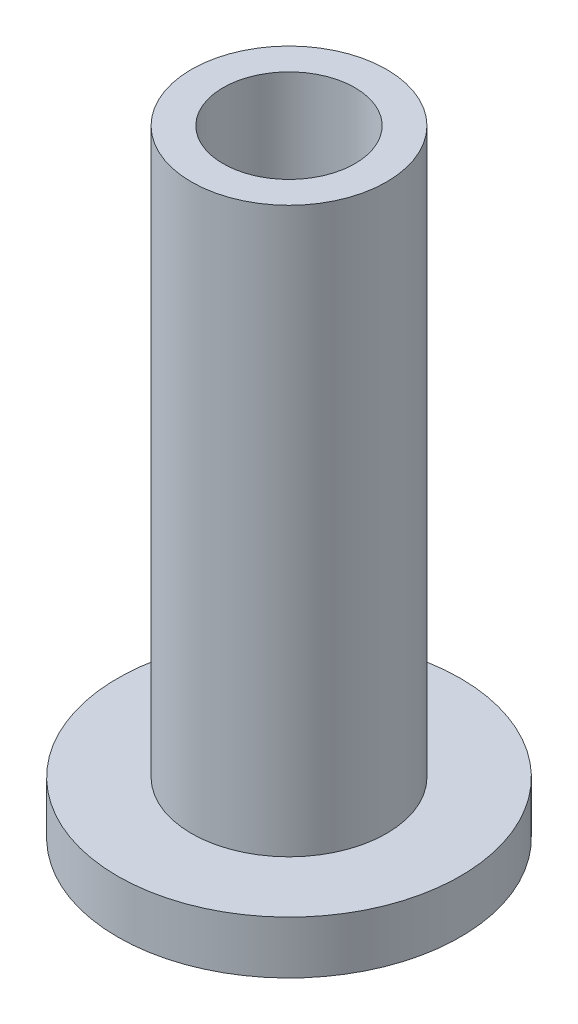
SolidWorks part; units mm, degrees
material "Delrin 2700 NC010, Low Viscosity Acetal Copolymer (SS)"
ref_plane "Front Plane" through (0, 0, 0) normal (0, 0, 1) x (1, 0, 0)
ref_plane "Top Plane" through (0, 0, 0) normal (0, 1, 0) x (1, 0, 0)
ref_plane "Right Plane" through (0, 0, 0) normal (1, 0, 0) x (0, 0, -1)
sketch "Sketch1" plane through (0, 0, 0) normal (0, 1, 0) x (1, 0, 0)
  circle A0 centre (0, 0) radius 4.1275
  dimension "D1" = 8.255
extrude "Boss-Extrude1" add sketch "Sketch1" along normal blind 1.27
sketch "Sketch2" plane through (0, 1.27, 0) normal (0, 1, 0) x (1, 0, 0)
  circle A0 centre (0, 0) radius 2.3495
  dimension "D1" = 4.699
extrude "Boss-Extrude2" add sketch "Sketch2" along normal blind 13.589
sketch "Sketch3" plane through (0, 0, 0) normal (0, -1, 0) x (1, 0, 0)
  circle A0 centre (0, 0) radius 1.5875
  dimension "D1" = 3.175
extrude "Cut-Extrude2" cut sketch "Sketch3" against normal through all
